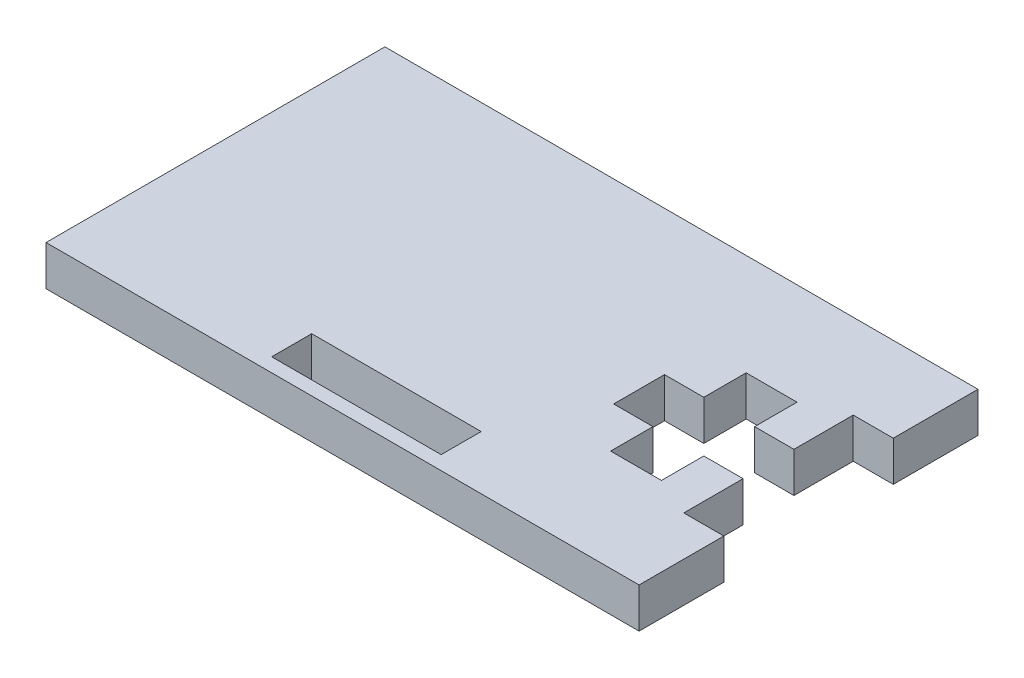
SolidWorks part; units mm, degrees
ref_plane "Front Plane" through (0, 0, 0) normal (0, 0, 1) x (1, 0, 0)
ref_plane "Top Plane" through (0, 0, 0) normal (0, 1, 0) x (1, 0, 0)
ref_plane "Right Plane" through (0, 0, 0) normal (1, 0, 0) x (0, 0, -1)
sketch "Sketch1" plane through (0, 0, 0) normal (0, 1, 0) x (1, 0, 0)
  line L0 (22.225, 6.35) -> (19.225, 6.35)
  line L1 (22.225, -12.7) -> (-22.225, -12.7)
  line L2 (22.225, -12.7) -> (22.225, -6.35)
  line L3 (22.225, 12.7) -> (-22.225, 12.7)
  line L4 (-22.225, -12.7) -> (-22.225, 12.7)
  line L5 (22.225, -12.7) -> (-22.225, 12.7) construction
  line L6 (22.225, 12.7) -> (-22.225, -12.7) construction
  line L7 (19.225, 6.35) -> (19.225, 1.905)
  line L8 (19.225, -6.35) -> (22.225, -6.35)
  line L9 (22.225, 6.35) -> (22.225, 12.7)
  line L10 (22.225, 6.35) -> (22.225, -6.35) construction
  line L11 (-22.225, 0) -> (22.225, 0) construction
  line L12 (9.525, 1.905) -> (12.47, 1.905)
  line L13 (9.525, 1.905) -> (9.525, -1.905)
  line L14 (9.525, -1.905) -> (12.47, -1.905)
  line L15 (12.47, 1.905) -> (12.47, 5.08)
  line L16 (9.525, 1.905) -> (19.225, -1.905) construction
  line L17 (9.525, -1.905) -> (19.225, 1.905) construction
  line L18 (19.225, -1.905) -> (19.225, -6.35)
  line L19 (16.28, -5.08) -> (12.47, -5.08)
  line L20 (16.28, -5.08) -> (16.28, -1.905)
  line L21 (16.28, 5.08) -> (12.47, 5.08)
  line L22 (12.47, -5.08) -> (12.47, -1.905)
  line L23 (16.28, 1.905) -> (19.225, 1.905)
  line L24 (16.28, 1.905) -> (16.28, 5.08)
  line L25 (16.28, -1.905) -> (19.225, -1.905)
  line L26 (12.47, 5.08) -> (16.28, -5.08) construction
  line L27 (16.28, 5.08) -> (12.47, -5.08) construction
  point P0 (0, 0)
  point P8 (14.375, 0)
  point P17 (9.525, 0)
  point P18 (14.375, 0)
  dimension "D1" = 44.45
  dimension "D2" = 25.4
  dimension "D3" = 12.7
  dimension "D4" = 3
  dimension "D5" = 3.81
  dimension "D6" = 6.35
  dimension "D7" = 12.7
  dimension "D9" = 3.81
  dimension "D10" = 10.16
extrude "Boss-Extrude1" add sketch "Sketch1" along normal blind 3
sketch "Sketch2" plane through (0, 3, 0) normal (0, 1, 0) x (1, 0, 0)
  line L0 (-22.225, -10.16) -> (22.225, -10.16) construction
  line L1 (-22.225, 12.7) -> (-22.225, -12.7) construction
  line L2 (22.225, -12.7) -> (22.225, -6.35) construction
  line L3 (-22.225, -12.7) -> (22.225, -12.7) construction
  line L5 (-6.35, -8.66) -> (6.35, -8.66)
  line L6 (-6.35, -8.66) -> (-6.35, -11.66)
  line L7 (-6.35, -11.66) -> (6.35, -11.66)
  line L8 (6.35, -8.66) -> (6.35, -11.66)
  line L9 (-6.35, -8.66) -> (6.35, -11.66) construction
  line L10 (-6.35, -11.66) -> (6.35, -8.66) construction
  point P8 (0, -10.16)
  dimension "D1" = 2.54
  dimension "D2" = 12.7
  dimension "D3" = 3
extrude "Cut-Extrude1" cut sketch "Sketch2" against normal through all
